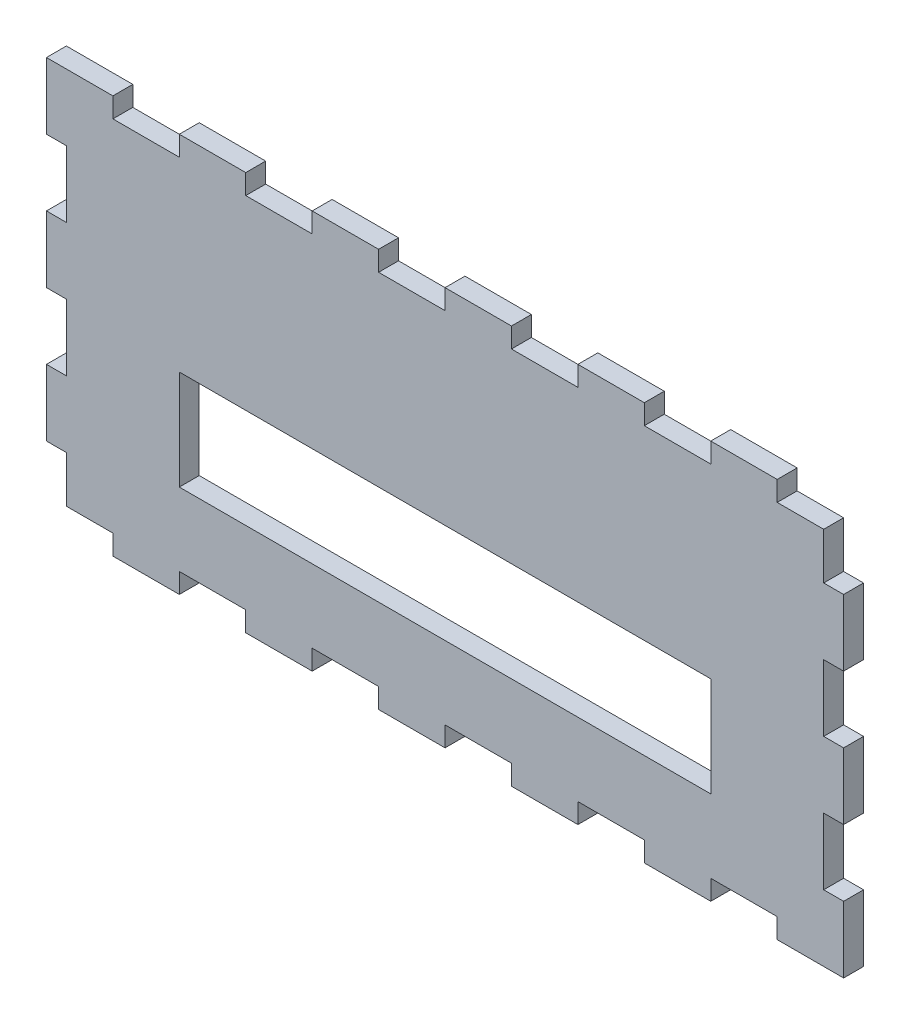
SolidWorks part; units mm, degrees
material "Beech"
ref_plane "Front Plane" through (0, 0, 0) normal (0, 0, 1) x (1, 0, 0)
ref_plane "Top Plane" through (0, 0, 0) normal (0, 1, 0) x (1, 0, 0)
ref_plane "Right Plane" through (0, 0, 0) normal (1, 0, 0) x (0, 0, -1)
sketch "Sketch1" plane through (0, 0, 0) normal (0, 0, 1) x (1, 0, 0)
  line L0 (120, 10) -> (117, 10)
  line L1 (0, 0) -> (120, 0)
  line L2 (0, 0) -> (0, 60)
  line L3 (0, 60) -> (120, 60)
  line L4 (120, 0) -> (120, 60)
  line L5 (117, 10) -> (117, 20)
  line L6 (117, 20) -> (120, 20)
  line L7 (117, 40) -> (120, 40)
  line L8 (117, 30) -> (117, 40)
  line L9 (120, 30) -> (117, 30)
  line L10 (117, 60) -> (120, 60)
  line L11 (117, 50) -> (117, 60)
  line L12 (120, 50) -> (117, 50)
  line L13 (3, 3) -> (10, 3)
  line L14 (10, 3) -> (10, 0)
  line L15 (20, 0) -> (20, 3)
  line L16 (20, 3) -> (30, 3)
  line L17 (30, 3) -> (30, 0)
  line L18 (40, 0) -> (40, 3)
  line L19 (40, 3) -> (50, 3)
  line L20 (50, 3) -> (50, 0)
  line L21 (60, 0) -> (60, 3)
  line L22 (60, 3) -> (70, 3)
  line L23 (70, 3) -> (70, 0)
  line L24 (80, 0) -> (80, 3)
  line L25 (80, 3) -> (90, 3)
  line L26 (90, 3) -> (90, 0)
  line L27 (100, 0) -> (100, 3)
  line L28 (100, 3) -> (110, 3)
  line L29 (110, 3) -> (110, 0)
  line L30 (110, 60) -> (110, 57)
  line L31 (110, 57) -> (117, 57)
  line L32 (100, 60) -> (100, 57)
  line L33 (100, 57) -> (90, 57)
  line L34 (0, 50) -> (3, 50)
  line L35 (3, 50) -> (3, 40)
  line L36 (3, 40) -> (0, 40)
  line L37 (3, 20) -> (0, 20)
  line L38 (3, 30) -> (3, 20)
  line L39 (0, 30) -> (3, 30)
  line L40 (3, 0) -> (0, 0)
  line L41 (3, 10) -> (3, 0)
  line L42 (0, 10) -> (3, 10)
  line L43 (90, 57) -> (90, 60)
  line L44 (80, 60) -> (80, 57)
  line L45 (80, 57) -> (70, 57)
  line L46 (70, 57) -> (70, 60)
  line L47 (60, 60) -> (60, 57)
  line L48 (60, 57) -> (50, 57)
  line L49 (50, 57) -> (50, 60)
  line L50 (40, 60) -> (40, 57)
  line L51 (40, 57) -> (30, 57)
  line L52 (30, 57) -> (30, 60)
  line L53 (20, 60) -> (20, 57)
  line L54 (20, 57) -> (10, 57)
  line L55 (10, 57) -> (10, 60)
  point P45 (110, 58.5)
  dimension "D1" = 120
  dimension "D2" = 60
  dimension "D3" = 5
  dimension "D4" = 10
  dimension "D5" = 10
  dimension "D7" = 10
  dimension "D8" = 3
  dimension "D9" = 10
  dimension "D11" = 10
  dimension "D12" = 10
  dimension "D13" = 3
  dimension "D10" = 10
  dimension "D15" = 3
  dimension "D16" = 3
  dimension "D17" = 10
  dimension "D18" = 10
  dimension "D19" = 10
  dimension "D20" = 3
  dimension "D22" = 5
  dimension "D14" = 3
  dimension "D6" = 3
extrude "Boss-Extrude1" add sketch "Sketch1" along normal blind 3
sketch "Sketch2" plane through (0, 0, 3) normal (0, 0, 1) x (1, 0, 0)
  line L0 (0, 10) -> (0, 20) construction
  line L1 (20, 14) -> (100, 14)
  line L2 (20, 14) -> (20, 29)
  line L3 (20, 29) -> (100, 29)
  line L4 (100, 14) -> (100, 29)
  line L5 (60, 3) -> (70, 3) construction
  dimension "D1" = 15
  dimension "D2" = 80
  dimension "D3" = 20
  dimension "D4" = 11
extrude "Cut-Extrude1" cut sketch "Sketch2" against normal blind 10
